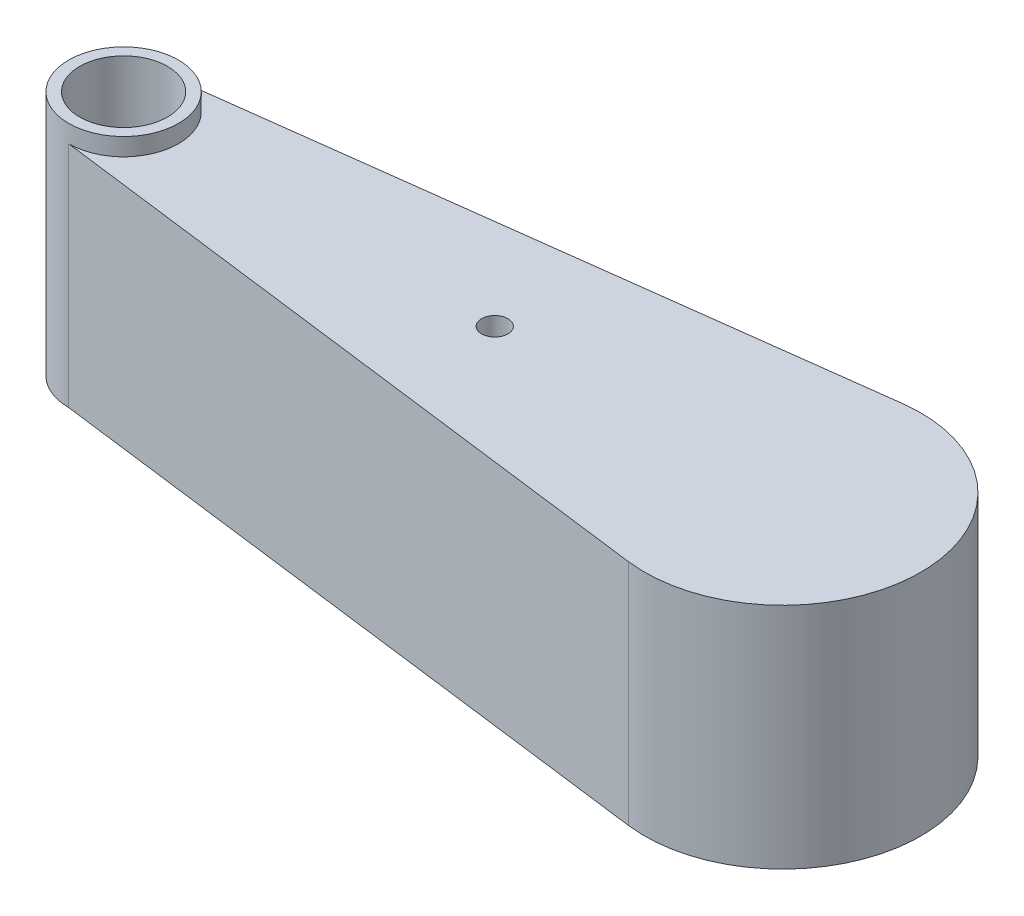
SolidWorks part; units mm, degrees
material "PE High Density"
ref_plane "Front Plane" through (0, 0, 0) normal (0, 0, 1) x (1, 0, 0)
ref_plane "Top Plane" through (0, 0, 0) normal (0, 1, 0) x (1, 0, 0)
ref_plane "Right Plane" through (0, 0, 0) normal (1, 0, 0) x (0, 0, -1)
sketch "Sketch1" plane through (0, 0, 0) normal (0, 1, 0) x (1, 0, 0)
  line L0 (-19.569, 0) -> (53.4391, 9.3326)
  line L1 (-19.569, -12.5) -> (53.4391, -21.8326)
  line L2 (71.1404, -6.25) -> (-25.819, -6.25) construction
  arc A0 (53.4391, 9.3326) -> (53.4391, -21.8326) centre (55.431, -6.25) cw
  arc A1 (-19.569, 0) -> (-19.569, -12.5) centre (-19.569, -6.25) ccw
  circle A2 centre (-19.569, -6.25) radius 5
  circle A3 centre (22.6607, -6.25) radius 1.5
  dimension "D1" = 6.25
  dimension "D2" = 10
  dimension "D4" = 3
  dimension "D3" = 75
extrude "Boss-Extrude2" add sketch "Sketch1" along normal blind 26
sketch "Sketch2" plane through (0, 26, 0) normal (0, 1, 0) x (1, 0, 0)
  line L0 (-19.569, 0) -> (-19.569, -12.5) construction
  arc A0 (-19.569, 0) -> (-19.569, -12.5) centre (-19.569, -6.25) ccw construction
  circle A1 centre (-19.569, -6.25) radius 6.25
extrude "Boss-Extrude3" add sketch "Sketch2" along normal blind 2
sketch "Sketch3" plane through (0, 28, 0) normal (0, 1, 0) x (1, 0, 0)
  circle A3 centre (-19.569, -6.25) radius 5
  circle A4 centre (-19.569, -6.25) radius 5
  dimension "D1" = 1.25
extrude "Cut-Extrude1" cut sketch "Sketch3" against normal blind 2
